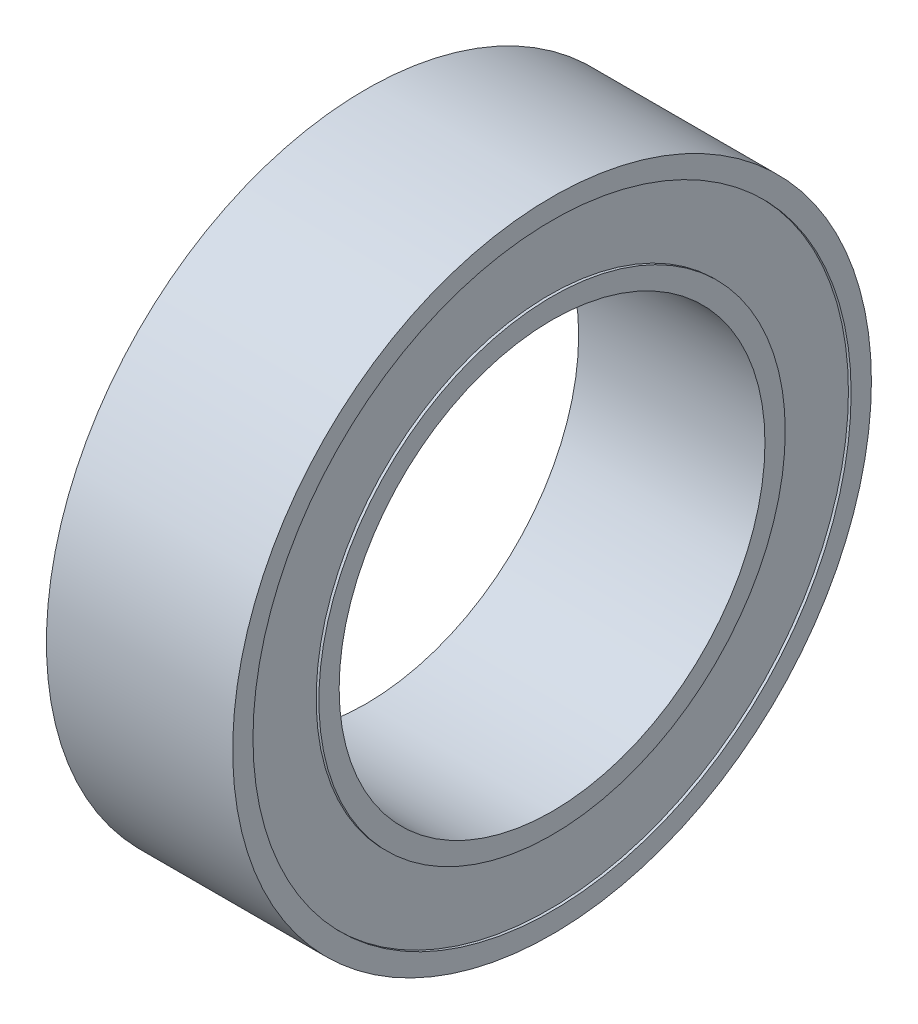
SolidWorks part; units mm, degrees
ref_plane "Front Plane" through (0, 0, 0) normal (0, 0, 1) x (1, 0, 0)
ref_plane "Top Plane" through (0, 0, 0) normal (0, 1, 0) x (1, 0, 0)
ref_plane "Right Plane" through (0, 0, 0) normal (1, 0, 0) x (0, 0, -1)
sketch "Sketch1" plane through (0, 0, 0) normal (1, 0, 0) x (0, 0, -1)
  circle A0 centre (0, 0) radius 6
  circle A1 centre (0, 0) radius 4
  dimension "D1" = 12
  dimension "D2" = 8
extrude "Boss-Extrude1" add sketch "Sketch1" along normal mid plane 3.5
sketch "Sketch2" plane through (1.75, 0, 0) normal (1, 0, 0) x (0, 0, -1)
  circle A2 centre (0, 0) radius 5.619
  circle A3 centre (0, 0) radius 5.619
  circle A5 centre (0, 0) radius 4.381
  circle A6 centre (0, 0) radius 4.381
  dimension "D1" = 0.381
  dimension "D2" = 0.381
extrude "Cut-Extrude1" cut sketch "Sketch2" against normal blind 0.0508
mirror "Mirror1" about plane through (0, 0, 0) normal (1, 0, 0) of "Cut-Extrude1"
